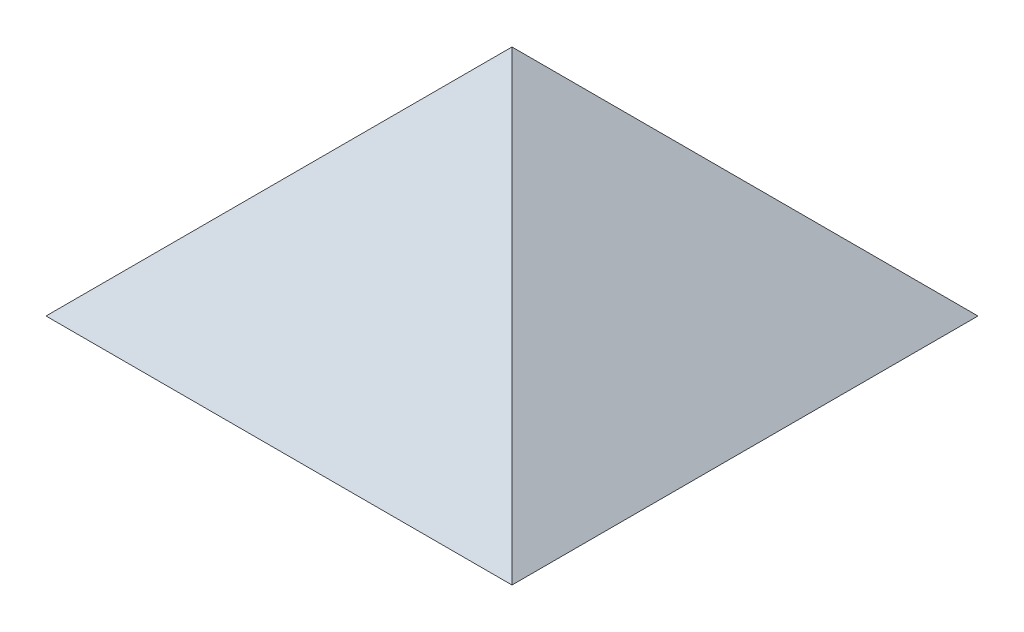
SolidWorks part; units mm, degrees
material "AISI 1020"
ref_plane "Front Plane" through (0, 0, 0) normal (0, 0, 1) x (1, 0, 0)
ref_plane "Top Plane" through (0, 0, 0) normal (0, 1, 0) x (1, 0, 0)
ref_plane "Right Plane" through (0, 0, 0) normal (1, 0, 0) x (0, 0, -1)
sketch "Sketch1" plane through (0, 0, 0) normal (0, 1, 0) x (1, 0, 0)
  line L1 (-50, -50) -> (50, -50)
  line L2 (-50, -50) -> (-50, 50)
  line L3 (-50, 50) -> (50, 50)
  line L4 (50, -50) -> (50, 50)
  line L5 (-50, -50) -> (50, 50) construction
  line L6 (-50, 50) -> (50, -50) construction
  point P0 (0, 0)
  dimension "D1" = 100
extrude "Boss-Extrude1" add sketch "Sketch1" along normal blind 100 draft 45
